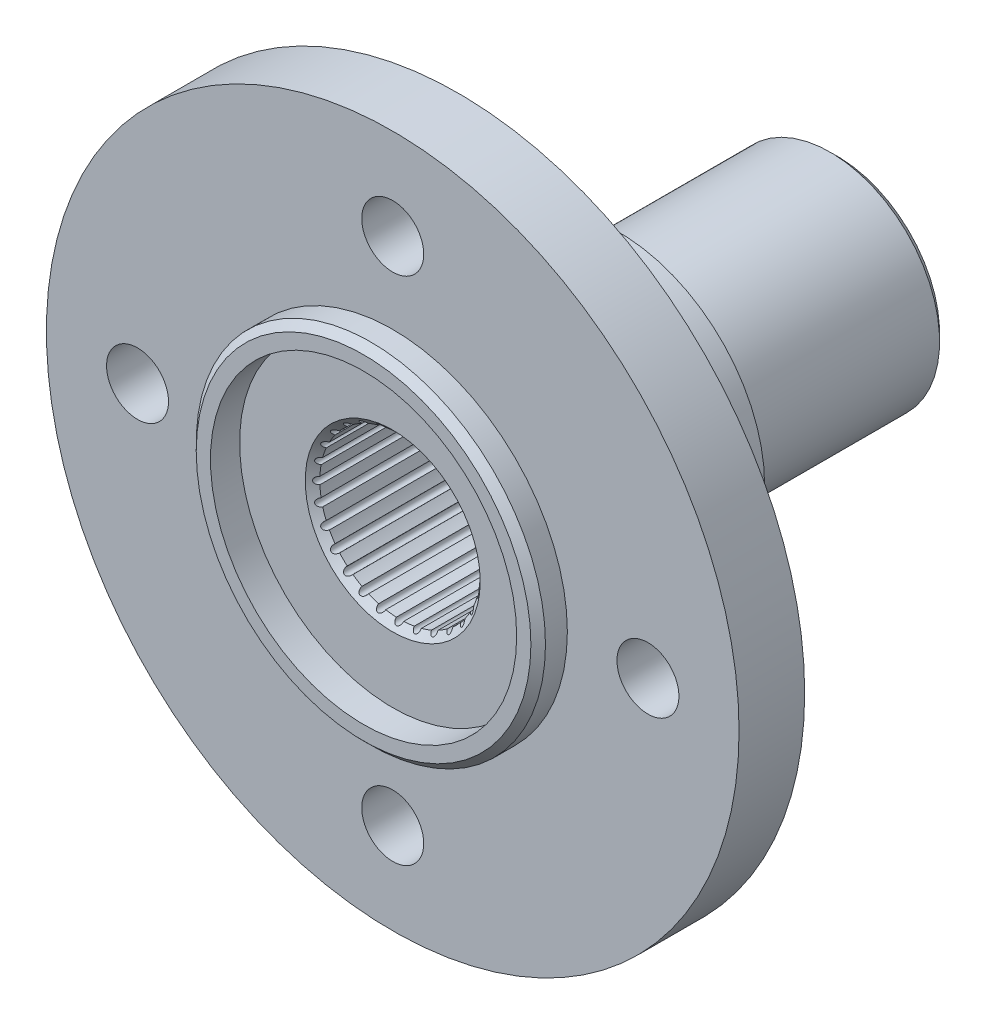
SolidWorks part; units mm, degrees
ref_plane "Ön Düzlem" through (0, 0, 0) normal (0, 0, 1) x (1, 0, 0)
ref_plane "Üst Düzlem" through (0, 0, 0) normal (0, 1, 0) x (1, 0, 0)
ref_plane "Sağ Düzlem" through (0, 0, 0) normal (1, 0, 0) x (0, 0, -1)
sketch "Sketch1" plane through (0, 0, 0) normal (0, 0, 1) x (1, 0, 0)
  circle A0 centre (0, 0) radius 47.5
  dimension "D1" = 95
extrude "Boss-Extrude1" add sketch "Sketch1" along normal blind 9
sketch "Sketch2" plane through (0, 0, 0) normal (0, 0, -1) x (-1, 0, 0)
  circle A0 centre (0, 0) radius 20
  dimension "D1" = 40
extrude "Boss-Extrude2" add sketch "Sketch2" along normal blind 22
sketch "Sketch3" plane through (0, 0, -22) normal (0, 0, -1) x (-1, 0, 0)
  circle A0 centre (0, 0) radius 15
  dimension "D1" = 30
extrude "Boss-Extrude3" add sketch "Sketch3" along normal blind 30
sketch "Sketch6" plane through (0, 0, -52) normal (0, 0, -1) x (-1, 0, 0)
  circle A0 centre (0, 0) radius 11
  dimension "D1" = 22
extrude "Cut-Extrude2" cut sketch "Sketch6" against normal blind 25
chamfer "Chamfer2" distance 1 1 edges at (-11, 0, -52)
sketch "Sketch9" plane through (0, 0, 9) normal (0, 0, 1) x (1, 0, 0)
  circle A0 centre (0, 35) radius 4.25
  circle A1 centre (35, 0) radius 4.25
  circle A2 centre (0, -35) radius 4.25
  circle A3 centre (-35, 0) radius 4.25
  point P12 (0, 0)
  dimension "D2" = 8.5
  dimension "D1" = 35
  dimension "D3" = 4
extrude "Cut-Extrude5" cut sketch "Sketch9" against normal up to next
chamfer "Chamfer3" distance 1 1 edges at (-15, 0, -52)
sketch "Sketch12" plane through (0, 0, 9) normal (0, 0, 1) x (1, 0, 0)
  circle A0 centre (0, 0) radius 23.95
  dimension "D1" = 47.9
extrude "Boss-Extrude4" add sketch "Sketch12" along normal blind 4
sketch "Sketch13" plane through (0, 0, 13) normal (0, 0, 1) x (1, 0, 0)
  circle A0 centre (0, 0) radius 21
  dimension "D1" = 42
extrude "Cut-Extrude6" cut sketch "Sketch13" against normal up to surface (4 mm away) up to face at (23.95, 0, 9)
chamfer "Chamfer4" distance 1 1 edges at (23.95, 0, 13)
sketch "Sketch8" plane through (0, 0, -52) normal (0, 0, -1) x (-1, 0, 0)
  circle A0 centre (0, 11) radius 0.5
  circle A1 centre (0, 0) radius 11 construction
  circle A2 centre (2.4477, 10.7242) radius 0.5
  circle A3 centre (4.7727, 9.9107) radius 0.5
  circle A4 centre (6.8584, 8.6001) radius 0.5
  circle A5 centre (8.6001, 6.8584) radius 0.5
  circle A6 centre (9.9107, 4.7727) radius 0.5
  circle A7 centre (10.7242, 2.4477) radius 0.5
  circle A8 centre (11, 0) radius 0.5
  circle A9 centre (10.7242, -2.4477) radius 0.5
  circle A10 centre (9.9107, -4.7727) radius 0.5
  circle A11 centre (8.6001, -6.8584) radius 0.5
  circle A12 centre (6.8584, -8.6001) radius 0.5
  circle A13 centre (4.7727, -9.9107) radius 0.5
  circle A14 centre (2.4477, -10.7242) radius 0.5
  circle A15 centre (0, -11) radius 0.5
  circle A16 centre (-2.4477, -10.7242) radius 0.5
  circle A17 centre (-4.7727, -9.9107) radius 0.5
  circle A18 centre (-6.8584, -8.6001) radius 0.5
  circle A19 centre (-8.6001, -6.8584) radius 0.5
  circle A20 centre (-9.9107, -4.7727) radius 0.5
  circle A21 centre (-10.7242, -2.4477) radius 0.5
  circle A22 centre (-11, 0) radius 0.5
  circle A23 centre (-10.7242, 2.4477) radius 0.5
  circle A24 centre (-9.9107, 4.7727) radius 0.5
  circle A25 centre (-8.6001, 6.8584) radius 0.5
  circle A26 centre (-6.8584, 8.6001) radius 0.5
  circle A27 centre (-4.7727, 9.9107) radius 0.5
  circle A28 centre (-2.4477, 10.7242) radius 0.5
  point P61 (0, 0)
  dimension "D1" = 1
  dimension "D2" = 28
extrude "Cut-Extrude4" cut sketch "Sketch8" against normal up to surface (25 mm away) up to face at (-11, 0, -27)
sketch "Sketch14" plane through (0, 0, -27) normal (0, 0, -1) x (-1, 0, 0)
  circle A0 centre (0, 0) radius 11
extrude "Cut-Extrude7" cut sketch "Sketch14" against normal through all
chamfer "Chamfer5" distance 1 1 edges at (11, 0, 9)
sketch "Sketch15" plane through (0, 0, -52) normal (0, 0, -1) x (-1, 0, 0)
  circle A1 centre (8.6001, 6.8584) radius 0.5
  circle A2 centre (8.6001, 6.8584) radius 0.5
  circle A3 centre (6.8584, 8.6001) radius 0.5
  circle A4 centre (6.8584, 8.6001) radius 0.5
  circle A5 centre (4.7727, 9.9107) radius 0.5
  circle A6 centre (4.7727, 9.9107) radius 0.5
  circle A7 centre (2.4477, 10.7242) radius 0.5
  circle A8 centre (2.4477, 10.7242) radius 0.5
  circle A9 centre (0, 11) radius 0.5
  circle A10 centre (0, 11) radius 0.5
  circle A11 centre (4.7727, -9.9107) radius 0.5
  circle A12 centre (4.7727, -9.9107) radius 0.5
  circle A13 centre (6.8584, -8.6001) radius 0.5
  circle A14 centre (6.8584, -8.6001) radius 0.5
  circle A15 centre (8.6001, -6.8584) radius 0.5
  circle A16 centre (8.6001, -6.8584) radius 0.5
  circle A17 centre (9.9107, -4.7727) radius 0.5
  circle A18 centre (9.9107, -4.7727) radius 0.5
  circle A19 centre (10.7242, -2.4477) radius 0.5
  circle A20 centre (10.7242, -2.4477) radius 0.5
  circle A21 centre (11, 0) radius 0.5
  circle A22 centre (11, 0) radius 0.5
  circle A23 centre (10.7242, 2.4477) radius 0.5
  circle A24 centre (10.7242, 2.4477) radius 0.5
  circle A25 centre (9.9107, 4.7727) radius 0.5
  circle A26 centre (9.9107, 4.7727) radius 0.5
  circle A27 centre (-10.7242, -2.4477) radius 0.5
  circle A28 centre (-10.7242, -2.4477) radius 0.5
  circle A29 centre (-9.9107, -4.7727) radius 0.5
  circle A30 centre (-9.9107, -4.7727) radius 0.5
  circle A31 centre (-8.6001, -6.8584) radius 0.5
  circle A32 centre (-8.6001, -6.8584) radius 0.5
  circle A33 centre (-6.8584, -8.6001) radius 0.5
  circle A34 centre (-6.8584, -8.6001) radius 0.5
  circle A35 centre (-4.7727, -9.9107) radius 0.5
  circle A36 centre (-4.7727, -9.9107) radius 0.5
  circle A37 centre (-2.4477, -10.7242) radius 0.5
  circle A38 centre (-2.4477, -10.7242) radius 0.5
  circle A39 centre (0, -11) radius 0.5
  circle A40 centre (0, -11) radius 0.5
  circle A41 centre (2.4477, -10.7242) radius 0.5
  circle A42 centre (2.4477, -10.7242) radius 0.5
  circle A43 centre (-2.4477, 10.7242) radius 0.5
  circle A44 centre (-2.4477, 10.7242) radius 0.5
  circle A45 centre (-4.7727, 9.9107) radius 0.5
  circle A46 centre (-4.7727, 9.9107) radius 0.5
  circle A47 centre (-6.8584, 8.6001) radius 0.5
  circle A48 centre (-6.8584, 8.6001) radius 0.5
  circle A49 centre (-8.6001, 6.8584) radius 0.5
  circle A50 centre (-8.6001, 6.8584) radius 0.5
  circle A51 centre (-9.9107, 4.7727) radius 0.5
  circle A52 centre (-9.9107, 4.7727) radius 0.5
  circle A53 centre (-10.7242, 2.4477) radius 0.5
  circle A54 centre (-10.7242, 2.4477) radius 0.5
  circle A55 centre (-11, 0) radius 0.5
  circle A56 centre (-11, 0) radius 0.5
  dimension "D1" = 0
  dimension "D2" = 0
  dimension "D3" = 0
  dimension "D4" = 0
  dimension "D5" = 0
  dimension "D6" = 0
  dimension "D7" = 0
  dimension "D8" = 0
  dimension "D9" = 0
  dimension "D10" = 0
  dimension "D11" = 0
  dimension "D12" = 0
  dimension "D13" = 0
  dimension "D14" = 0
  dimension "D15" = 0
  dimension "D16" = 0
  dimension "D17" = 0
  dimension "D18" = 0
  dimension "D19" = 0
  dimension "D20" = 0
  dimension "D21" = 0
  dimension "D22" = 0
  dimension "D23" = 0
  dimension "D24" = 0
  dimension "D25" = 0
  dimension "D26" = 0
  dimension "D27" = 0
  dimension "D28" = 0
extrude "Cut-Extrude8" cut sketch "Sketch15" against normal through all
